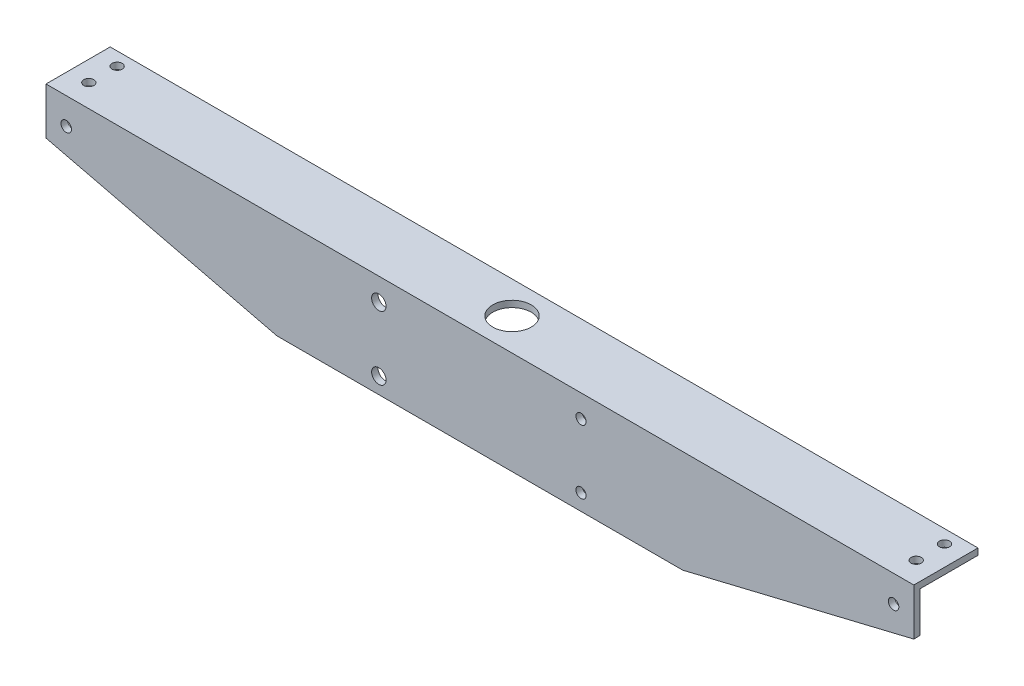
SolidWorks part; units mm, degrees
material "6063-T5"
ref_plane "Front Plane" through (0, 0, 0) normal (0, 0, 1) x (1, 0, 0)
ref_plane "Top Plane" through (0, 0, 0) normal (0, 1, 0) x (1, 0, 0)
ref_plane "Right Plane" through (0, 0, 0) normal (1, 0, 0) x (0, 0, -1)
sketch "Sketch1" plane through (0, 0, 0) normal (1, 0, 0) x (0, 0, -1)
  line L0 (0, 0) -> (31.75, 0)
  line L1 (31.75, 0) -> (31.75, -3.175)
  line L2 (31.75, -3.175) -> (3.175, -3.175)
  line L3 (3.175, -3.175) -> (3.175, -50.8)
  line L4 (3.175, -50.8) -> (0, -50.8)
  line L5 (0, -50.8) -> (0, 0)
  dimension "D1" = 31.75
  dimension "D2" = 3.175
  dimension "D3" = 3.175
  dimension "D4" = 50.8
extrude "Boss-Extrude1" add sketch "Sketch1" along normal mid plane 429.26
sketch "Sketch2" plane through (0, 0, -3.175) normal (0, 0, -1) x (-1, 0, 0)
  line L0 (0, 0) -> (0, -57.8721) construction
  line L1 (-214.63, -50.8) -> (214.63, -50.8) construction
  line L3 (-214.63, -3.175) -> (214.63, -3.175) construction
  circle A0 centre (-50, -11.175) radius 2.5
  circle A1 centre (50, -11.175) radius 3.57
  circle A2 centre (50, -42.8) radius 3.57
  circle A3 centre (-50, -42.8) radius 2.5
  dimension "D1" = 5
  dimension "D2" = 5
  dimension "D3" = 7.14
  dimension "D4" = 7.14
  dimension "D7" = 8
  dimension "D9" = 8
  dimension "D5" = 50
  dimension "D6" = 50
extrude "Cut-Extrude1" cut sketch "Sketch2" against normal through all
sketch "Sketch3" plane through (0, 0, -3.175) normal (0, 0, -1) x (-1, 0, 0)
  line L0 (214.63, -50.8) -> (100.33, -50.8)
  line L1 (-214.63, -50.8) -> (214.63, -50.8) construction
  line L2 (100.33, -50.8) -> (214.63, -23.175)
  line L3 (214.63, -50.8) -> (214.63, -3.175) construction
  line L4 (214.63, -23.175) -> (214.63, -50.8)
  line L5 (-214.63, -23.175) -> (-214.63, -50.8)
  line L6 (0, 0) -> (0, -50.8) construction
  line L7 (-100.33, -50.8) -> (-214.63, -23.175)
  line L8 (-214.63, -50.8) -> (-100.33, -50.8)
  dimension "D1" = 20
  dimension "D2" = 114.3
extrude "Cut-Extrude2" cut sketch "Sketch3" against normal blind 3.175
sketch "Sketch4" plane through (0, 0, 0) normal (0, 1, 0) x (1, 0, 0)
  line L0 (0, 0) -> (0, 31.75) construction
  line L1 (214.63, 31.75) -> (-214.63, 31.75) construction
  line L2 (-214.63, 31.75) -> (-214.63, 0) construction
  line L4 (214.63, 0) -> (-214.63, 0) construction
  circle A0 centre (-204.63, 11.176) radius 2.5
  circle A1 centre (-204.63, 25.176) radius 2.5
  circle A2 centre (204.63, 25.176) radius 2.5
  circle A3 centre (204.63, 11.176) radius 2.5
  dimension "D1" = 5
  dimension "D2" = 5
  dimension "D3" = 10
  dimension "D4" = 11.176
  dimension "D5" = 14
extrude "Cut-Extrude3" cut sketch "Sketch4" against normal blind 3.175
sketch "Sketch5" plane through (0, -3.175, 0) normal (0, -1, 0) x (1, 0, 0)
  line L0 (214.63, 0) -> (-214.63, 0) construction
  circle A0 centre (0, -15.875) radius 19.05 construction
  circle A1 centre (0, -15.875) radius 9.525
  dimension "D1" = 19.05
  dimension "D2" = 38.1
  dimension "D3" = 15.875
extrude "Cut-Extrude4" cut sketch "Sketch5" against normal up to next
sketch "Sketch6" plane through (0, 0, 0) normal (0, 0, 1) x (1, 0, 0)
  line L0 (214.63, 0) -> (214.63, -23.175) construction
  line L1 (214.63, 0) -> (-214.63, 0) construction
  line L2 (0, 0) -> (0, -50.8) construction
  line L3 (100.33, -50.8) -> (-100.33, -50.8) construction
  circle A0 centre (204.63, -13.175) radius 2.6
  circle A1 centre (-204.63, -13.175) radius 2.6
  dimension "D1" = 5.2
  dimension "D3" = 13.175
  dimension "D2" = 10
extrude "Cut-Extrude5" cut sketch "Sketch6" against normal up to surface (3.175 mm away) up to face at (50, -40.3, -3.175)
equation "\"D2@Sketch2\"=\"D1@Sketch2\""
equation "\"D4@Sketch2\"=\"D3@Sketch2\""
equation "\"D2@Sketch4\" = \"D1@Sketch4\""
